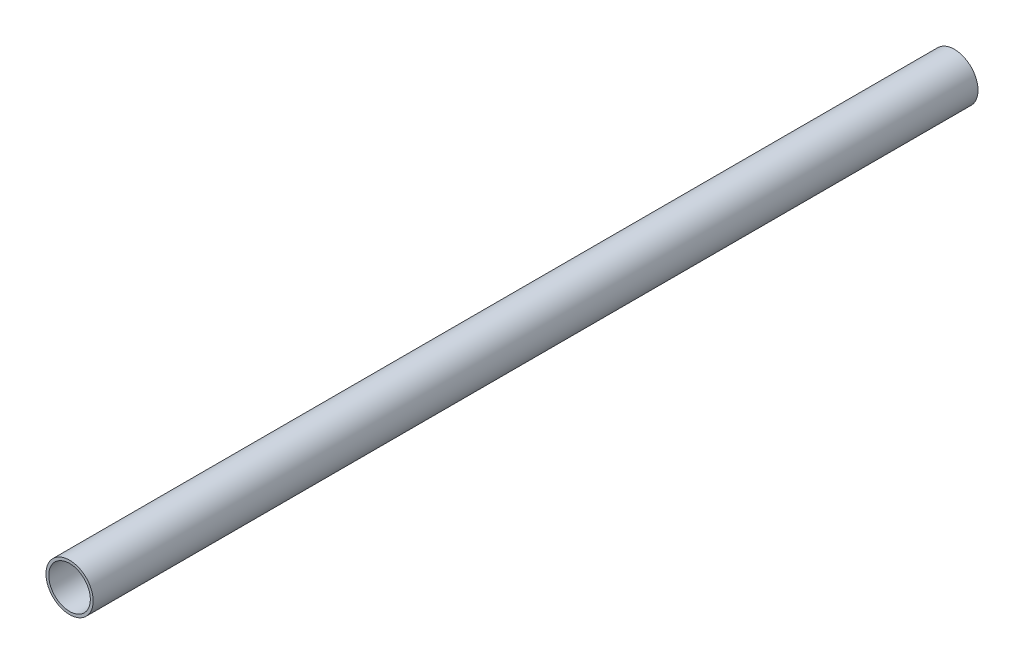
SolidWorks part; units mm, degrees
material "PE Высокой плотности"
ref_plane "Front" through (0, 0, 0) normal (0, 0, 1) x (1, 0, 0)
ref_plane "Top" through (0, 0, 0) normal (0, 1, 0) x (1, 0, 0)
ref_plane "Side" through (0, 0, 0) normal (1, 0, 0) x (0, 0, -1)
sketch "PipeSketch" plane through (0, 0, 0) normal (0, 0, 1) x (1, 0, 0)
  circle A0 centre (0, 0) radius 16
  circle A1 centre (0, 0) radius 14.1
  dimension "OuterDiameter" = 32
  dimension "InnerDiameter" = 28.2
extrude "Extrusion" add sketch "PipeSketch" along normal blind 600
sketch "FilterSketch" plane through (0, 0, 0) normal (0, 0, 1) x (1, 0, 0)
  circle A0 centre (0, 0) radius 16 construction
  dimension "NominalDiameter" = 32
